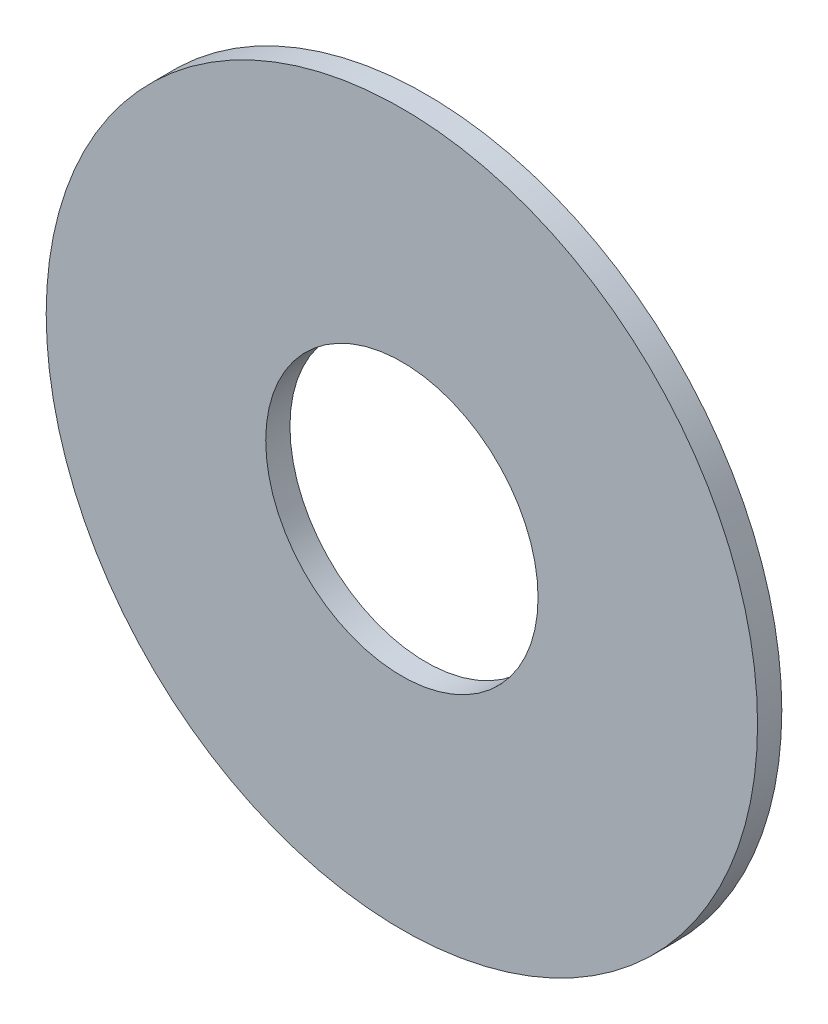
SolidWorks part; units mm, degrees
ref_plane "Front Plane" through (0, 0, 0) normal (0, 0, 1) x (1, 0, 0)
ref_plane "Top Plane" through (0, 0, 0) normal (0, 1, 0) x (1, 0, 0)
ref_plane "Right Plane" through (0, 0, 0) normal (1, 0, 0) x (0, 0, -1)
sketch "Sketch1" plane through (0, 0, 0) normal (0, 0, 1) x (1, 0, 0)
  circle A0 centre (0, 0) radius 9.3218
  circle A1 centre (0, 0) radius 3.5687
  point P5 (0, -9.3218)
  dimension "OD" = 18.6436
  dimension "ID" = 7.1374
sketch "Sketch2" plane through (0, 0, 0) normal (1, 0, 0) x (0, 0, -1)
  line L0 (-0.3175, 0) -> (0.3175, 0) construction
  point P0 (-0.3175, -9.3218)
  point P4 (0, 0)
  point P6 (0.3175, -9.3218)
  dimension "Thickness Range" = 0.635
sketch "Sketch3" plane through (0, 0, 0) normal (0, 0, 1) x (1, 0, 0)
  circle A0 centre (0, 0) radius 9.3218 construction
  circle A1 centre (0, 0) radius 3.5687 construction
  circle A2 centre (0, 0) radius 9.3218
  circle A3 centre (0, 0) radius 3.5687
extrude "Boss-Extrude1" add sketch "Sketch3" along normal up to vertex (0.3175 mm away) and the other way up to vertex (0.3175 mm away) up to point (0, -9.3218, 0.3175) other way up to point (0, -9.3218, -0.3175)
